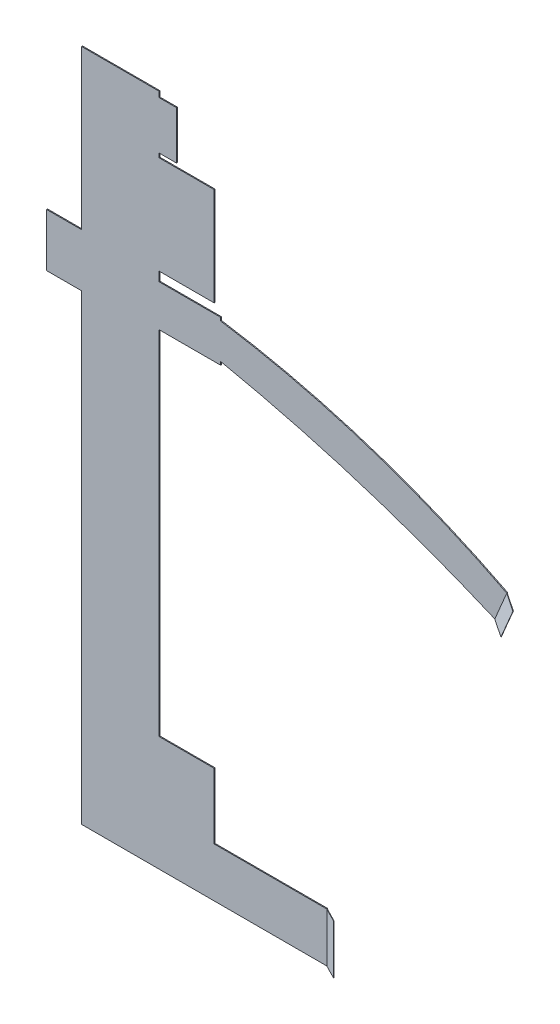
SolidWorks part; units mm, degrees
ref_plane "前视基准面" through (0, 0, 0) normal (0, 0, 1) x (1, 0, 0)
ref_plane "上视基准面" through (0, 0, 0) normal (0, 1, 0) x (1, 0, 0)
ref_plane "右视基准面" through (0, 0, 0) normal (1, 0, 0) x (0, 0, -1)
ref_plane "基准面4"
sketch "草图1" plane through (0, 0, 42) normal (0, 0, 1) x (1, 0, 0)
  line L0 (849.2, -450.2) -> (849.2, -502.2)
  line L1 (849.2, -502.2) -> (868.2, -502.2)
  line L2 (868.2, -502.2) -> (868.2, -450.2)
  line L3 (868.2, -450.2) -> (849.2, -450.2)
  line L4 (909.2, -1091.6) -> (849.2, -1091.6)
  line L5 (849.2, -1091.6) -> (849.2, -1121.1)
  line L6 (849.2, -1121.1) -> (909.2, -1121.1)
  line L7 (909.2, -1121.1) -> (909.2, -1091.6)
  line L8 (849.2, -1050.1) -> (849.2, -1091.6)
  line L9 (849.2, -1091.6) -> (909.2, -1091.6)
  line L10 (909.2, -1091.6) -> (909.2, -1050.1)
  line L11 (909.2, -1050.1) -> (849.2, -1050.1)
  line L12 (825.5, -1174.6) -> (825.5, -1125.1)
  line L13 (825.5, -1125.1) -> (765.5, -1125.1)
  line L14 (765.5, -1125.1) -> (765.5, -1174.6)
  line L15 (765.5, -1174.6) -> (825.5, -1174.6)
  line L16 (765.5, -504.2) -> (825.5, -504.2)
  line L17 (825.5, -504.2) -> (825.5, -444.2)
  line L18 (825.5, -444.2) -> (765.5, -444.2)
  line L19 (765.5, -444.2) -> (765.5, -504.2)
  line L20 (849.2, -506.7) -> (849.2, -613.1)
  line L21 (849.2, -613.1) -> (909.2, -613.1)
  line L22 (909.2, -613.1) -> (909.2, -506.7)
  line L23 (909.2, -506.7) -> (849.2, -506.7)
  line L24 (765.5, -1008.6) -> (825.5, -1008.6)
  line L25 (825.5, -1008.6) -> (825.5, -897.6)
  line L26 (825.5, -897.6) -> (765.5, -897.6)
  line L27 (765.5, -897.6) -> (765.5, -1008.6)
  line L28 (765.5, -897.6) -> (825.5, -897.6)
  line L29 (825.5, -897.6) -> (825.5, -786.6)
  line L30 (825.5, -786.6) -> (765.5, -786.6)
  line L31 (765.5, -786.6) -> (765.5, -897.6)
  line L32 (765.5, -616.2) -> (825.5, -616.2)
  line L33 (825.5, -616.2) -> (825.5, -504.2)
  line L34 (825.5, -504.2) -> (765.5, -504.2)
  line L35 (765.5, -504.2) -> (765.5, -616.2)
  line L36 (765.5, -786.6) -> (825.5, -786.6)
  line L37 (825.5, -786.6) -> (825.5, -673.6)
  line L38 (825.5, -673.6) -> (765.5, -673.6)
  line L39 (765.5, -673.6) -> (765.5, -786.6)
  line L40 (765.5, -1125.1) -> (825.5, -1125.1)
  line L41 (825.5, -1125.1) -> (825.5, -1008.6)
  line L42 (825.5, -1008.6) -> (765.5, -1008.6)
  line L43 (765.5, -1008.6) -> (765.5, -1125.1)
  line L44 (909.2, -1121.1) -> (849.2, -1121.1)
  line L45 (849.2, -1121.1) -> (849.2, -1174.6)
  line L46 (849.2, -1174.6) -> (1031.2, -1174.6)
  line L47 (1031.2, -1174.6) -> (1031.2, -1121.1)
  line L48 (1031.2, -1121.1) -> (909.2, -1121.1)
  line L49 (849.2, -623.1) -> (849.2, -668.1)
  line L50 (849.2, -668.1) -> (916.2, -668.1)
  line L51 (916.2, -668.1) -> (916.2, -664.6)
  line L52 (1213.4, -757.7) -> (1226.4, -727)
  line L53 (916.2, -626.6) -> (916.2, -623.1)
  line L54 (916.2, -623.1) -> (849.2, -623.1)
  line L55 (765.5, -616.2) -> (727.5, -616.2)
  line L56 (727.5, -616.2) -> (727.5, -673.6)
  line L57 (727.5, -673.6) -> (765.5, -673.6)
  line L58 (765.5, -673.6) -> (825.5, -673.6)
  line L59 (825.5, -673.6) -> (825.5, -786.6)
  line L60 (825.5, -786.6) -> (825.5, -897.6)
  line L61 (825.5, -897.6) -> (825.5, -1008.6)
  line L62 (825.5, -1008.6) -> (825.5, -1125.1)
  line L63 (825.5, -1125.1) -> (825.5, -1174.6)
  line L64 (825.5, -1174.6) -> (849.2, -1174.6)
  line L65 (849.2, -1174.6) -> (849.2, -1121.1)
  line L66 (849.2, -1121.1) -> (849.2, -1091.6)
  line L67 (849.2, -1091.6) -> (849.2, -1050.1)
  line L68 (849.2, -1050.1) -> (849.2, -681.1)
  line L69 (849.2, -681.1) -> (849.2, -668.1)
  line L70 (849.2, -668.1) -> (849.2, -623.1)
  line L71 (849.2, -623.1) -> (849.2, -613.1)
  line L72 (849.2, -613.1) -> (849.2, -506.7)
  line L73 (849.2, -506.7) -> (849.2, -502.2)
  line L74 (849.2, -502.2) -> (849.2, -450.2)
  line L75 (849.2, -450.2) -> (849.2, -444.2)
  line L76 (849.2, -444.2) -> (825.5, -444.2)
  line L77 (825.5, -444.2) -> (825.5, -504.2)
  line L78 (825.5, -504.2) -> (825.5, -616.2)
  line L79 (825.5, -616.2) -> (765.5, -616.2)
  arc A0 (1213.4, -757.7) -> (916.2, -664.6) centre (605.6007, -2177.0365) ccw
  arc A1 (1226.4, -727) -> (916.2, -626.6) centre (761.993, -1632.4479) ccw
  dimension "D35" = 1017.6
  dimension "D38" = 1544
  dimension "D1" = 38
  dimension "D2" = 60
  dimension "D3" = 112
  dimension "D4" = 60
  dimension "D5" = 60
  dimension "D6" = 23.7
  dimension "D7" = 6
  dimension "D8" = 19
  dimension "D9" = 52
  dimension "D10" = 4.5
  dimension "D11" = 60
  dimension "D12" = 106.4
  dimension "D13" = 113
  dimension "D14" = 60
  dimension "D15" = 111
  dimension "D16" = 111
  dimension "D17" = 60
  dimension "D18" = 116.5
  dimension "D19" = 60
  dimension "D20" = 49.5
  dimension "D21" = 23.7
  dimension "D22" = 10
  dimension "D23" = 67
  dimension "D24" = 3.5
  dimension "D25" = 45
  dimension "D26" = 3.5
  dimension "D27" = 13
  dimension "D28" = 369
  dimension "D29" = 60
  dimension "D30" = 41.5
  dimension "D31" = 29.5
  dimension "D32" = 182
  dimension "D33" = 326.0432
  dimension "D34" = 326.0432
  dimension "D36" = 311.4409
  dimension "D37" = 311.4409
extrude "拉伸1" add sketch "草图1" against normal blind 1 contours L2 L3 L0 L1 | L6 L7 L4 L5 | L10 L11 L8 L4 | L14 L15 L12 L13 | L18 L19 L16 L17 | L22 L23 L20 L21 | L26 L27 L24 L25 | L30 L31 L26 L29 | L16 L35 L32 L33 | L38 L39 L30 L37 | L24 L43 L13 L41 | L47 L48 L6 L45 L46 | L52 A1 L53 L54 L49 L50 L51 A0 | L75 L76 L17 L33 L32 L55 L56 L57 L38 L37 L29 L25 L41 L12 L64 L45 L5 L8 L68 L69 L49 L71 L20 L73 L0
sketch "草图2" plane through (0, -1174.6, 0) normal (0, -1, 0) x (1, 0, 0)
  line L0 (1031.2, 42) -> (1046.2, 49.6486)
  line L1 (1046.2, 49.6486) -> (1046.2, 49.1486)
  line L2 (1046.2, 49.1486) -> (1031.2, 41.5)
  line L3 (1031.2, 41.5) -> (1031.2, 42)
  line L4 (1031.2, 41) -> (1031.2, 42) construction
  line L5 (765.5, 42) -> (1031.2, 42) construction
  dimension "D1" = 15
  dimension "D3" = 0.5
extrude "拉伸2" add sketch "草图2" against normal up to surface (53.5 mm away) up to face at (970.2, -1121.1, 41.5)
ref_plane "基准面5"
sketch "草图3" plane through (1226.4, -727, 42) normal (0.3899, 0.9208, 0) x (-0.9208, 0.3899, 0)
  line L0 (0, -0.5) -> (-15.5, 7.15)
  line L1 (-15.5, 7.15) -> (-15.5, 7.65)
  line L2 (-15.5, 7.65) -> (0, 0)
  line L3 (0, 0) -> (0, -0.5)
  line L4 (0, -1) -> (0, 0) construction
  dimension "D1" = 15.5
  dimension "D2" = 7.65
  dimension "D3" = 0.5
extrude "拉伸3" add sketch "草图3" against normal blind 33.4
